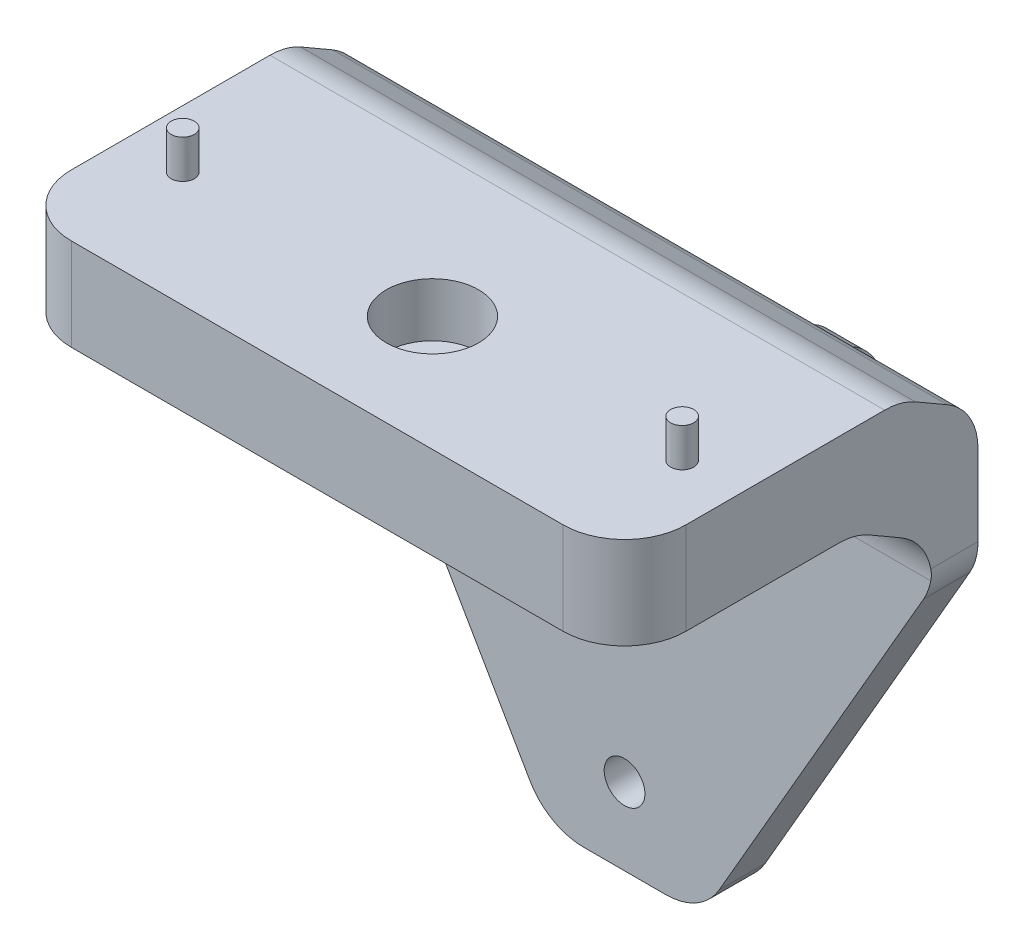
SolidWorks part; units mm, degrees
ref_plane "Front Plane" through (0, 0, 0) normal (0, 0, 1) x (1, 0, 0)
ref_plane "Top Plane" through (0, 0, 0) normal (0, 1, 0) x (1, 0, 0)
ref_plane "Right Plane" through (0, 0, 0) normal (1, 0, 0) x (0, 0, -1)
sketch "Sketch1" plane through (0, 0, 0) normal (1, 0, 0) x (0, 0, -1)
  line L0 (0, 0) -> (40, 0)
  line L1 (40, 0) -> (40, -63)
  line L2 (40, -63) -> (46, -63)
  line L3 (46, -63) -> (46, 12)
  line L4 (46, 12) -> (0, 12)
  line L5 (0, 12) -> (0, 0)
  dimension "D1" = 75
  dimension "D2" = 40
  dimension "D3" = 6
  dimension "D4" = 12
extrude "Boss-Extrude1" add sketch "Sketch1" along normal mid plane 80
sketch "Sketch2" plane through (0, 0, 0) normal (0, -1, 0) x (1, 0, 0)
  line L0 (40, 0) -> (-40, 0) construction
  circle A0 centre (0, -15) radius 2.65
  dimension "D2" = 5.3
  dimension "D1" = 15
extrude "Cut-Extrude2" cut sketch "Sketch2" against normal up to surface (12 mm away) up to face at (0, 12, -23)
sketch "Sketch3" plane through (0, 12, 0) normal (0, 1, 0) x (1, 0, 0)
  circle A0 centre (0, 15) radius 6
  dimension "D1" = 12
extrude "Cut-Extrude3" cut sketch "Sketch3" against normal blind 7
sketch "Sketch4" plane through (0, 0, -40) normal (0, 0, 1) x (1, 0, 0)
  line L0 (40, -63) -> (-40, -63) construction
  line L1 (40, 0) -> (-40, 0) construction
  circle A0 centre (0, -53) radius 2.65
  circle A1 centre (0, -25) radius 2.65
  point P4 (0, -63)
  dimension "D1" = 5.3
  dimension "D2" = 10
  dimension "D3" = 25
extrude "Cut-Extrude4" cut sketch "Sketch4" against normal up to next
chamfer "Chamfer2" distance 30 angle 60 2 edges at (-40, -63, -43) (40, -63, -43)
sketch "Sketch7" plane through (0, 0, -46) normal (0, 0, -1) x (-1, 0, 0)
  line L0 (-40, 12) -> (40, 12) construction
  line L1 (-12.7, 0) -> (-17.7, 0)
  line L2 (-12.7, 0) -> (-12.7, -40)
  line L3 (-12.7, -40) -> (-17.7, -40)
  line L4 (-17.7, 0) -> (-17.7, -40)
  circle A0 centre (0, -25) radius 2.65 construction
  dimension "D1" = 5
  dimension "D2" = 12.7
  dimension "D3" = 12
  dimension "D4" = 40
extrude "Boss-Extrude3" add sketch "Sketch7" along normal blind 10
chamfer "Chamfer1" distance 10 angle 30 2 edges at (0, 12, -46) (0, 0, -40)
fillet "Fillet1" radius 8 4 edges at (0, -5.7735, -40) (0, 0, -30) (0, 12, -36) (0, 6.2265, -46)
fillet "Fillet2" radius 8 6 edges at (-40, 6, 0) (40, 6, 0) (-40, -11.0385, -43) (40, -11.0385, -43) (10, -63, -43) (-10, -63, -43)
sketch "Sketch5" plane through (0, 12, 0) normal (0, 1, 0) x (1, 0, 0)
  line L0 (32.5, 15) -> (0, 15) construction
  line L1 (0, 15) -> (-32.5, 15) construction
  circle A0 centre (-32.5, 15) radius 1.5
  circle A1 centre (32.5, 15) radius 1.5
  dimension "D1" = 65
  dimension "D2" = 3
extrude "Boss-Extrude2" add sketch "Sketch5" along normal blind 5
fillet "Fillet3" radius 8 2 edges at (15.2, -40, -56) (15.2, 0, -56)
